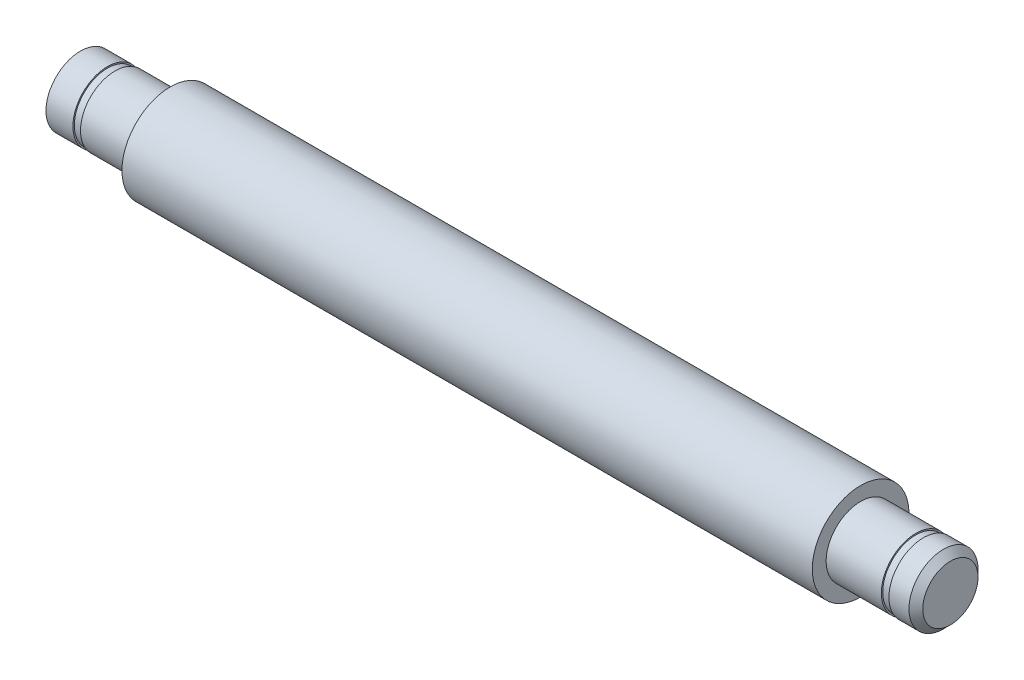
SolidWorks part; units mm, degrees
ref_plane "Ebene vorne" through (0, 0, 0) normal (0, 0, 1) x (1, 0, 0)
ref_plane "Ebene oben" through (0, 0, 0) normal (0, 1, 0) x (1, 0, 0)
ref_plane "Ebene rechts" through (0, 0, 0) normal (1, 0, 0) x (0, 0, -1)
sketch "Skizze1" plane through (0, 0, 0) normal (0, 1, 0) x (1, 0, 0)
  line L0 (-125.234, 0) -> (167.3763, 0) construction
  line L2 (-63, -5) -> (-50, -5)
  line L3 (-50, -5) -> (-50, -7)
  line L8 (63, 0) -> (-63, 0)
  line L11 (-63, -5) -> (-63, 0)
  line L13 (50, -5) -> (63, -5)
  line L14 (63, -5) -> (63, 0)
  line L22 (-50, -7) -> (50, -7)
  line L25 (0, 0) -> (0, -7) construction
  line L27 (50, -7) -> (50, -5)
  point P2 (51.9477, -6.5456)
  point P13 (51.8919, -6.3515)
  point P15 (51.9923, -6.8252)
  point P16 (51.9492, -6.5521)
  point P18 (50.0988, -7)
  dimension "D1" = 13
  dimension "D2" = 14
  dimension "D3" = 13
  dimension "D4" = 10
  dimension "D5" = 100
  dimension "D6" = 10
revolve "Rotation1" add sketch "Skizze1" angle 360 about L0
sketch "Skizze2" plane through (0, 0, 0) normal (0, 1, 0) x (1, 0, 0)
  line L0 (58, -5) -> (58, -4.8)
  line L1 (50, -5) -> (63, -5) construction
  line L2 (58, -4.8) -> (59.1, -4.8)
  line L3 (59.1, -4.8) -> (59.1, -5)
  line L4 (59.1, -5) -> (58, -5)
  line L5 (0, 0) -> (112.914, 0) construction
  line L7 (0, 0) -> (0, -7) construction
  line L9 (-59.1, -5) -> (-58, -5)
  line L10 (-59.1, -4.8) -> (-59.1, -5)
  line L11 (-58, -4.8) -> (-59.1, -4.8)
  line L12 (-58, -5) -> (-58, -4.8)
  line L14 (-50, -7) -> (50, -7) construction
  line L15 (50, -7) -> (50, 7) construction
  point P14 (0, -7)
  point P15 (0, -7)
  dimension "D1" = 9.6
  dimension "D2" = 1.1
  dimension "D3" = 8
revolve "Schnitt-Rotation1" cut sketch "Skizze2" angle 360 about L5
chamfer "Fase1" distance 1 angle 45 1 edges at (63, 0, 5)
